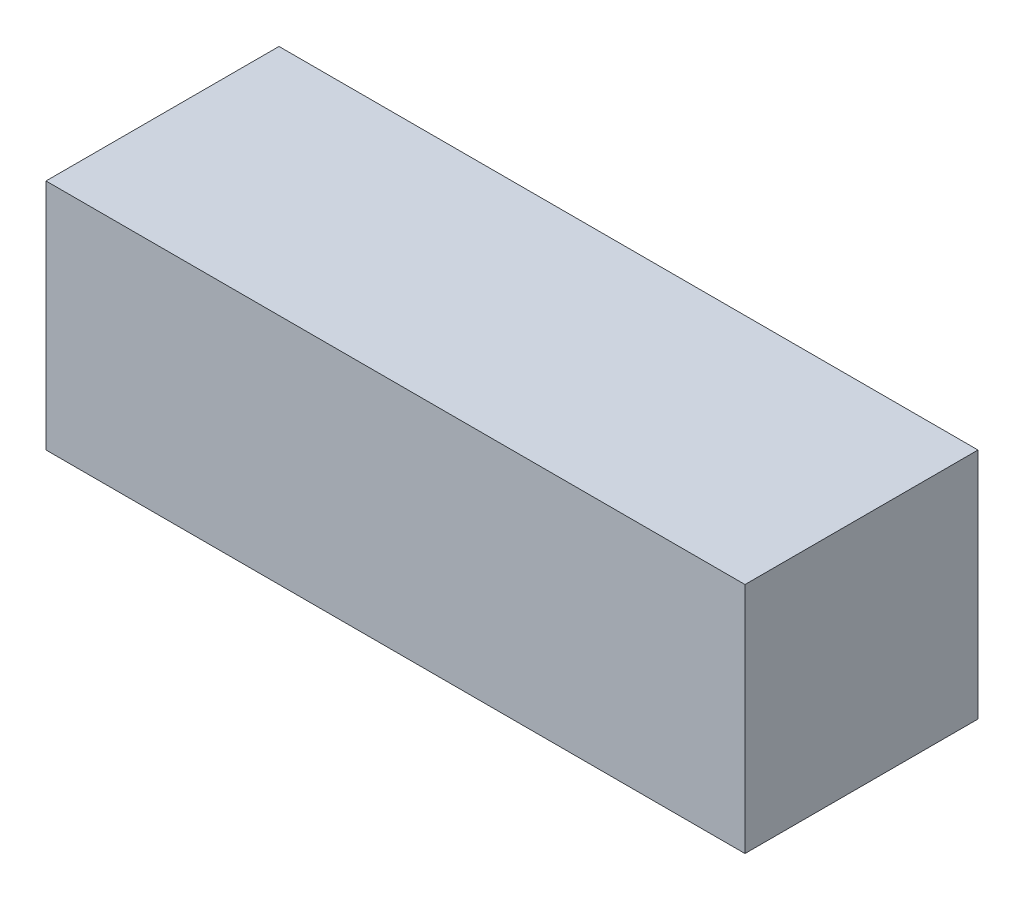
SolidWorks part; units mm, degrees
material "6061 Alloy"
ref_plane "Front Plane" through (0, 0, 0) normal (0, 0, 1) x (1, 0, 0)
ref_plane "Top Plane" through (0, 0, 0) normal (0, 1, 0) x (1, 0, 0)
ref_plane "Right Plane" through (0, 0, 0) normal (1, 0, 0) x (0, 0, -1)
sketch "Payload Structure Profile" plane through (0, 0, 0) normal (0, 0, 1) x (1, 0, 0)
  line L1 (0, 0) -> (300, 0)
  line L2 (0, 0) -> (0, 100)
  line L3 (0, 100) -> (300, 100)
  line L4 (300, 0) -> (300, 100)
  dimension "D1" = 300
  dimension "D2" = 100
extrude "Payload Structure Body" add sketch "Payload Structure Profile" along normal blind 100
